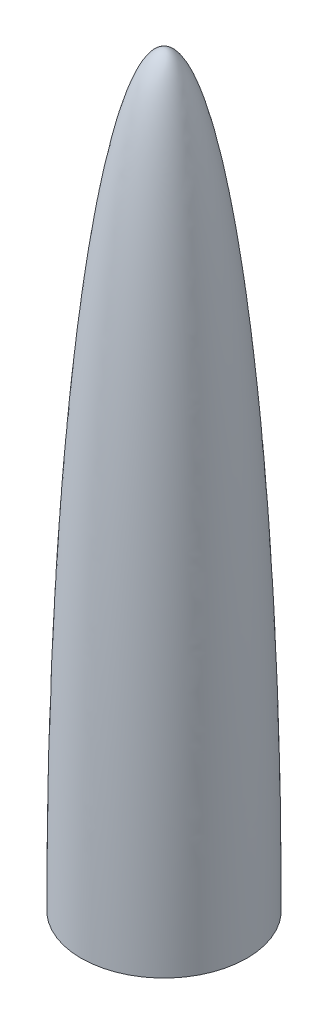
SolidWorks part; units mm, degrees
ref_plane "Front Plane" through (0, 0, 0) normal (0, 0, 1) x (1, 0, 0)
ref_plane "Top Plane" through (0, 0, 0) normal (0, 1, 0) x (1, 0, 0)
ref_plane "Right Plane" through (0, 0, 0) normal (1, 0, 0) x (0, 0, -1)
sketch "Sketch2" plane through (0, 0, 0) normal (1, 0, 0) x (0, 0, -1)
  line L0 (0, 228.6) -> (0, 227.33)
  line L1 (24.13, 0) -> (25.4, 0)
  line L2 (0, 0) -> (0, 228.6) construction
  ellipse E0 centre (0, 0) end of major axis (0, 228.6) minor radius 25.4 (25.4, 0) -> (0, 228.6) ccw
  ellipse E1 centre (0, 0) end of major axis (0, 227.33) minor radius 24.13 (24.13, 0) -> (0, 227.33) ccw
  dimension "D1" = 25.4
  dimension "D2" = 228.6
  dimension "D3" = 1.27
  dimension "D4" = 1.27
revolve "Revolve1" add sketch "Sketch2" angle 360 about L2
